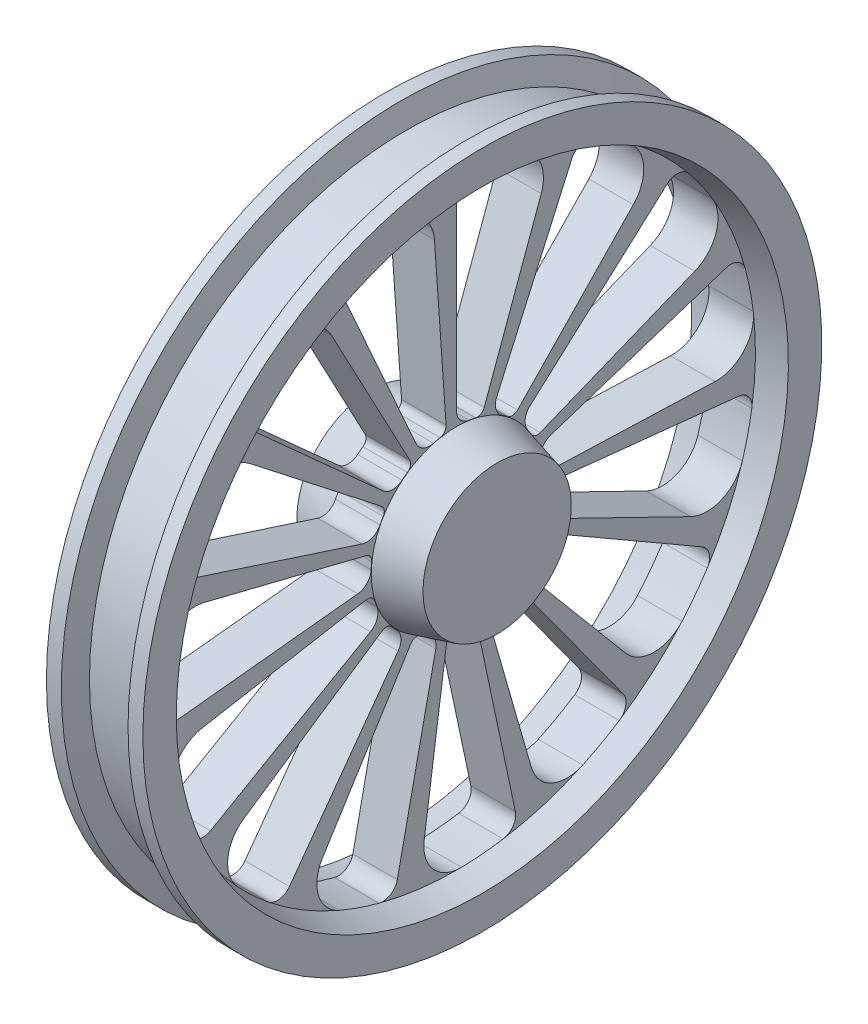
SolidWorks part; units mm, degrees
ref_plane "Front Plane" through (0, 0, 0) normal (0, 0, 1) x (1, 0, 0)
ref_plane "Top Plane" through (0, 0, 0) normal (0, 1, 0) x (1, 0, 0)
ref_plane "Right Plane" through (0, 0, 0) normal (1, 0, 0) x (0, 0, -1)
sketch "Sketch1" plane through (0, 0, 0) normal (0, 1, 0) x (1, 0, 0)
  line L0 (0, 0) -> (302.1461, 0) construction
  line L1 (0, 0) -> (0, 100)
  line L2 (0, 100) -> (55, 114.7372)
  line L3 (55, 114.7372) -> (55, 403.1218)
  line L4 (55, 403.1218) -> (20, 412.5)
  line L5 (20, 412.5) -> (20, 457.5)
  line L6 (20, 457.5) -> (40, 457.5)
  line L7 (40, 457.5) -> (48.0385, 427.5)
  line L8 (48.0385, 427.5) -> (121.9615, 427.5)
  line L9 (85, 482.751) -> (85, 0) construction
  line L10 (130, 457.5) -> (121.9615, 427.5)
  line L11 (150, 457.5) -> (130, 457.5)
  line L12 (150, 412.5) -> (150, 457.5)
  line L13 (115, 403.1218) -> (150, 412.5)
  line L14 (115, 114.7372) -> (115, 403.1218)
  line L15 (170, 100) -> (115, 114.7372)
  line L16 (170, 0) -> (170, 100)
  line L17 (0, 0) -> (170, 0)
  point P14 (85, 427.5)
  dimension "D1" = 200
  dimension "D2" = 75
  dimension "D3" = 60
  dimension "D4" = 45
  dimension "D5" = 915
  dimension "D6" = 105
  dimension "D7" = 170
  dimension "D8" = 20
  dimension "D9" = 75
  dimension "D10" = 130
  dimension "D11" = 30
revolve "Revolve1" add sketch "Sketch1" angle 360 about L17
sketch "Sketch2" plane through (115, 0, 0) normal (1, 0, 0) x (0, 0, -1)
  line L0 (-457.5, 0) -> (457.5, 0) construction
  line L1 (0, 457.5) -> (0, -457.5) construction
  line L2 (114.4038, 329.5251) -> (37.5491, 118.3684)
  line L3 (0, 382.5994) -> (0, 133.5103)
  line L4 (238.543, 254.5039) -> (82.4475, 92.8623)
  line L5 (155.6172, 349.5219) -> (54.3035, 121.9677)
  line L6 (321.436, 135.4767) -> (113.0901, 51.2995)
  line L7 (284.3268, 256.009) -> (99.2175, 89.3358)
  line L8 (348.7497, -6.9757) -> (124.1783, 0.8666)
  line L9 (363.8736, 118.2297) -> (126.9758, 41.257)
  line L10 (315.7614, -148.2219) -> (113.795, -49.7162)
  line L11 (380.5035, -39.9925) -> (132.7789, -13.9556)
  line L12 (228.1752, -263.8392) -> (83.7355, -91.7026)
  line L13 (331.3408, -191.2997) -> (115.6233, -66.7551)
  line L14 (101.1353, -333.8363) -> (39.1973, -117.8328)
  line L15 (224.8863, -309.5294) -> (78.4754, -108.0121)
  line L16 (-43.3917, -346.1101) -> (-12.1184, -123.5886)
  line L17 (79.5469, -374.2387) -> (27.7584, -130.5928)
  line L18 (-180.4159, -298.5383) -> (-61.3387, -107.9748)
  line L19 (-79.5469, -374.2387) -> (-27.7584, -130.5928)
  line L20 (-286.2446, -199.3465) -> (-99.953, -73.6912)
  line L21 (-224.8863, -309.5294) -> (-78.4754, -108.0121)
  line L22 (-342.579, -65.6859) -> (-121.2846, -26.6657)
  line L23 (-331.3408, -191.2997) -> (-115.6233, -66.7551)
  line L24 (-339.6784, 79.3324) -> (-121.6449, 24.9705)
  line L25 (-380.5035, -39.9925) -> (-132.7789, -13.9556)
  line L26 (-278.0442, 210.6334) -> (-100.9717, 72.2891)
  line L27 (-363.8736, 118.2297) -> (-126.9758, 41.257)
  line L28 (-168.3338, 305.5139) -> (-62.8396, 107.1083)
  line L29 (-284.3268, 256.009) -> (-99.2175, 89.3358)
  line L30 (-29.5168, 347.5684) -> (-13.842, 123.4075)
  line L31 (-155.6172, 349.5219) -> (-54.3035, 121.9677)
  circle A0 centre (0, 0) radius 457.5 construction
  arc A1 (0, 133.5103) -> (17.037, 113.731) centre (20, 133.5103) ccw
  arc A3 (76.9654, 395.7063) -> (21.0441, 402.5721) centre (0, 0) ccw
  arc A4 (21.0441, 402.5721) -> (0, 382.5994) centre (20, 382.5994) ccw
  arc A5 (25.9, 112.0455) -> (37.5491, 118.3684) centre (28.1521, 121.7886) ccw
  arc A6 (114.4038, 329.5251) -> (76.9654, 395.7063) centre (67.4192, 346.6261) ccw
  arc A7 (69.2338, 91.8242) -> (82.4475, 92.8623) centre (75.2541, 99.8089) ccw
  arc A8 (25.9, 112.0455) -> (17.037, 113.731) centre (0, 0) ccw
  arc A9 (238.543, 254.5039) -> (231.2596, 330.1911) centre (202.576, 289.2368) ccw
  arc A10 (231.2596, 330.1911) -> (182.9655, 359.2085) centre (0, 0) ccw
  arc A11 (182.9655, 359.2085) -> (155.6172, 349.5219) centre (173.8881, 341.3872) ccw
  arc A12 (54.3035, 121.9677) -> (61.8227, 96.9688) centre (72.5744, 113.833) ccw
  arc A13 (69.2338, 91.8242) -> (61.8227, 96.9688) centre (0, 0) ccw
  arc A14 (100.5965, 55.7256) -> (113.0901, 51.2995) centre (109.344, 60.5713) ccw
  arc A15 (321.436, 135.4767) -> (345.567, 207.5828) centre (302.7056, 181.8359) ccw
  arc A16 (345.567, 207.5828) -> (313.2506, 253.7345) centre (0, 0) ccw
  arc A17 (313.2506, 253.7345) -> (284.3268, 256.009) centre (297.7094, 241.1461) ccw
  arc A18 (99.2175, 89.3358) -> (95.9186, 63.4399) centre (112.6001, 74.4729) ccw
  arc A19 (100.5965, 55.7256) -> (95.9186, 63.4399) centre (0, 0) ccw
  arc A20 (114.5651, 9.9916) -> (124.1783, 0.8666) centre (124.5273, 10.8605) ccw
  arc A21 (348.7497, -6.9757) -> (400.1227, 49.0816) centre (350.4947, 42.9939) ccw
  arc A22 (400.1227, 49.0816) -> (389.3718, 104.3875) centre (0, 0) ccw
  arc A23 (389.3718, 104.3875) -> (363.8736, 118.2297) centre (370.054, 99.2086) ccw
  arc A24 (126.9758, 41.257) -> (113.4293, 18.9416) centre (133.1562, 22.2358) ccw
  arc A25 (114.5651, 9.9916) -> (113.4293, 18.9416) centre (0, 0) ccw
  arc A26 (108.7244, -37.47) -> (113.795, -49.7162) centre (118.1787, -40.7283) ccw
  arc A27 (315.7614, -148.2219) -> (385.4935, -117.9063) centre (337.68, -103.2822) ccw
  arc A28 (385.4935, -117.9063) -> (398.1671, -63.009) centre (0, 0) ccw
  arc A29 (398.1671, -63.009) -> (380.5035, -39.9925) centre (378.4129, -59.883) ccw
  arc A30 (132.7789, -13.9556) -> (111.3271, -28.8318) centre (130.6883, -33.8461) ccw
  arc A31 (108.7244, -37.47) -> (111.3271, -28.8318) centre (0, 0) ccw
  arc A32 (84.0843, -78.4528) -> (83.7355, -91.7026) centre (91.3959, -85.2748) ccw
  arc A33 (228.1752, -263.8392) -> (304.2091, -264.5071) centre (266.4774, -231.6998) ccw
  arc A34 (304.2091, -264.5071) -> (338.1157, -219.5107) centre (0, 0) ccw
  arc A35 (338.1157, -219.5107) -> (331.3408, -191.2997) centre (321.3408, -208.6202) ccw
  arc A36 (115.6233, -66.7551) -> (89.9754, -71.62) centre (105.6233, -84.0757) ccw
  arc A37 (84.0843, -78.4528) -> (89.9754, -71.62) centre (0, 0) ccw
  arc A38 (44.9052, -105.8703) -> (39.1973, -117.8328) centre (48.81, -115.0764) ccw
  arc A39 (101.1353, -333.8363) -> (170.3241, -365.3723) centre (149.1984, -320.0544) ccw
  arc A40 (170.3241, -365.3723) -> (219.601, -338.0571) centre (0, 0) ccw
  arc A41 (219.601, -338.0571) -> (224.8863, -309.5294) centre (208.7059, -321.2851) ccw
  arc A42 (78.4754, -108.0121) -> (53.0661, -102.0244) centre (62.295, -119.7678) ccw
  arc A43 (44.9052, -105.8703) -> (53.0661, -102.0244) centre (0, 0) ccw
  arc A44 (-2.0384, -114.9819) -> (-12.1184, -123.5886) centre (-2.2157, -124.9804) ccw
  arc A45 (-43.3917, -346.1101) -> (6.9885, -403.0612) centre (6.1217, -353.0687) ccw
  arc A46 (6.9885, -403.0612) -> (63.1153, -398.1503) centre (0, 0) ccw
  arc A47 (63.1153, -398.1503) -> (79.5469, -374.2387) centre (59.9839, -378.3969) ccw
  arc A48 (27.7584, -130.5928) -> (6.9813, -114.7879) centre (8.1954, -134.751) ccw
  arc A49 (-2.0384, -114.9819) -> (6.9813, -114.7879) centre (0, 0) ccw
  arc A50 (-48.6296, -104.2121) -> (-61.3387, -107.9748) centre (-52.8582, -113.274) ccw
  arc A51 (-180.4159, -298.5383) -> (-157.5555, -371.0572) centre (-138.0135, -325.0342) ccw
  arc A52 (-157.5555, -371.0572) -> (-104.2836, -389.3997) centre (0, 0) ccw
  arc A53 (-104.2836, -389.3997) -> (-79.5469, -374.2387) centre (-99.1098, -370.0804) ccw
  arc A54 (-27.7584, -130.5928) -> (-40.3107, -107.7035) centre (-47.3213, -126.4345) ccw
  arc A55 (-48.6296, -104.2121) -> (-40.3107, -107.7035) centre (0, 0) ccw
  arc A56 (-86.8122, -75.4231) -> (-99.953, -73.6912) centre (-94.3611, -81.9816) ccw
  arc A57 (-286.2446, -199.3465) -> (-294.8566, -274.894) centre (-258.285, -240.7984) ccw
  arc A58 (-294.8566, -274.894) -> (-253.651, -313.3183) centre (0, 0) ccw
  arc A59 (-253.651, -313.3183) -> (-224.8863, -309.5294) centre (-241.0666, -297.7737) ccw
  arc A60 (-78.4754, -108.0121) -> (-80.6327, -81.9962) centre (-94.6557, -96.2564) ccw
  arc A61 (-86.8122, -75.4231) -> (-80.6327, -81.9962) centre (0, 0) ccw
  arc A62 (-109.9842, -33.5927) -> (-121.2846, -26.6657) centre (-119.5481, -36.5138) ccw
  arc A63 (-342.579, -65.6859) -> (-381.1744, -131.1992) centre (-333.8966, -114.9263) ccw
  arc A64 (-381.1744, -131.1992) -> (-359.1597, -183.0614) centre (0, 0) ccw
  arc A65 (-359.1597, -183.0614) -> (-331.3408, -191.2997) centre (-341.3408, -173.9792) ccw
  arc A66 (-115.6233, -66.7551) -> (-107.0124, -42.111) centre (-125.6233, -49.4346) ccw
  arc A67 (-109.9842, -33.5927) -> (-107.0124, -42.111) centre (0, 0) ccw
  arc A68 (-114.139, 14.0461) -> (-121.6449, 24.9705) centre (-124.0641, 15.2675) ccw
  arc A69 (-339.6784, 79.3324) -> (-401.5837, 35.1812) centre (-351.7745, 30.8176) ccw
  arc A70 (-401.5837, 35.1812) -> (-402.5665, -21.1515) centre (0, 0) ccw
  arc A71 (-402.5665, -21.1515) -> (-380.5035, -39.9925) centre (-382.594, -20.1021) ccw
  arc A72 (-132.7789, -13.9556) -> (-114.8888, 5.0556) centre (-134.8695, 5.9348) ccw
  arc A73 (-114.139, 14.0461) -> (-114.8888, 5.0556) centre (0, 0) ccw
  arc A74 (-98.5581, 59.2563) -> (-100.9717, 72.2891) centre (-107.1283, 64.409) ccw
  arc A75 (-278.0442, 210.6334) -> (-352.5555, 195.4784) centre (-308.8273, 171.2328) ccw
  arc A76 (-352.5555, 195.4784) -> (-376.3659, 144.4157) centre (0, 0) ccw
  arc A77 (-376.3659, 144.4157) -> (-363.8736, 118.2297) centre (-357.6933, 137.2508) ccw
  arc A78 (-126.9758, 41.257) -> (-102.8999, 51.348) centre (-120.7955, 60.2781) ccw
  arc A79 (-98.5581, 59.2563) -> (-102.8999, 51.348) centre (0, 0) ccw
  arc A80 (-65.9356, 94.2205) -> (-62.8396, 107.1083) centre (-71.6691, 102.4136) ccw
  arc A81 (-168.3338, 305.5139) -> (-242.5672, 321.9756) centre (-212.4811, 282.0403) ccw
  arc A82 (-242.5672, 321.9756) -> (-285.0882, 285.0121) centre (0, 0) ccw
  arc A83 (-285.0882, 285.0121) -> (-284.3268, 256.009) centre (-270.9441, 270.8719) ccw
  arc A84 (-99.2175, 89.3358) -> (-73.1186, 88.7619) centre (-85.8349, 104.1987) ccw
  arc A85 (-65.9356, 94.2205) -> (-73.1186, 88.7619) centre (0, 0) ccw
  arc A86 (-21.9122, 112.8931) -> (-13.842, 123.4075) centre (-23.8176, 122.7099) ccw
  arc A87 (-29.5168, 347.5684) -> (-90.6369, 392.8004) centre (-79.395, 344.0805) ccw
  arc A88 (-90.6369, 392.8004) -> (-144.5161, 376.3273) centre (0, 0) ccw
  arc A89 (-144.5161, 376.3273) -> (-155.6172, 349.5219) centre (-137.3463, 357.6567) ccw
  arc A90 (-54.3035, 121.9677) -> (-30.6945, 110.828) centre (-36.0326, 130.1025) ccw
  arc A91 (-21.9122, 112.8931) -> (-30.6945, 110.828) centre (0, 0) ccw
  point P191 (0, 0)
  dimension "D1" = 15
  dimension "D2" = 40
  dimension "D3" = 806.2436
  dimension "D4" = 40
  dimension "D7" = 100
  dimension "D8" = 10
  dimension "D6" = 20
extrude "Cut-Extrude1" cut sketch "Sketch2" against normal through all and the other way through all contours L30 A86 A91 A90 L31 A89 A88 A87 | A5 L2 A6 A3 A4 L3 A1 A8 | L4 A7 A13 A12 L5 A11 A10 A9 | L6 A14 A19 A18 L7 A17 A16 A15 | L8 A20 A25 A24 L9 A23 A22 A21 | L10 A26 A31 A30 L11 A29 A28 A27 | L12 A32 A37 A36 L13 A35 A34 A33 | L14 A38 A43 A42 L15 A41 A40 A39 | L16 A44 A49 A48 L17 A47 A46 A45 | L18 A50 A55 A54 L19 A53 A52 A51 | L20 A56 A61 A60 L21 A59 A58 A57 | L22 A62 A67 A66 L23 A65 A64 A63 | L24 A68 A73 A72 L25 A71 A70 A69 | L26 A74 A79 A78 L27 A77 A76 A75 | L28 A80 A85 A84 L29 A83 A82 A81
equation "\"A\"= 130mm"
equation "\"B\"= 915mm"
